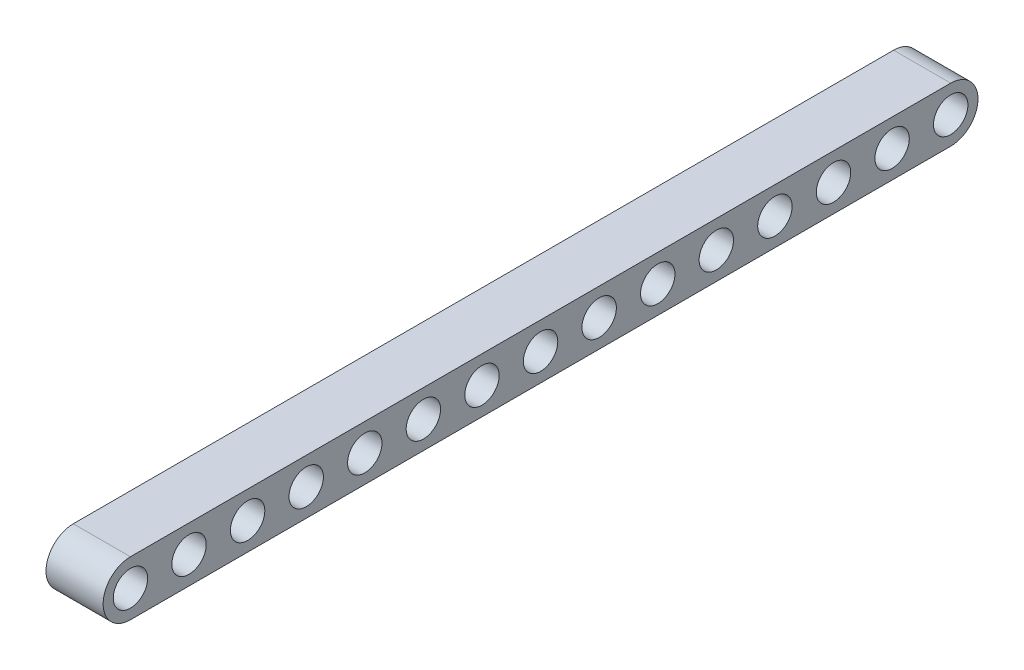
SolidWorks part; units mm, degrees
ref_plane "Front Plane" through (0, 0, 0) normal (0, 0, 1) x (1, 0, 0)
ref_plane "Top Plane" through (0, 0, 0) normal (0, 1, 0) x (1, 0, 0)
ref_plane "Right Plane" through (0, 0, 0) normal (1, 0, 0) x (0, 0, -1)
sketch "Sketch1" plane through (0, 0, 0) normal (1, 0, 0) x (0, 0, -1)
  line L0 (-56, 0) -> (56, 0) construction
  line L1 (-56, 3.73) -> (56, 3.73) construction
  line L2 (-56, 3.73) -> (-56, -3.73) construction
  line L3 (-56, -3.73) -> (56, -3.73) construction
  line L4 (56, 3.73) -> (56, -3.73) construction
  line L5 (-56, 3.73) -> (56, -3.73) construction
  line L6 (-56, -3.73) -> (56, 3.73) construction
  line L8 (-56, -3.73) -> (56, -3.73)
  line L10 (-56, 3.73) -> (56, 3.73)
  line L12 (-56, -3.73) -> (56, 3.73) construction
  line L13 (-56, 3.73) -> (56, -3.73) construction
  circle A0 centre (-56, 0) radius 2.35
  circle A1 centre (-48, 0) radius 2.35
  circle A2 centre (-40, 0) radius 2.35
  circle A3 centre (-32, 0) radius 2.35
  circle A4 centre (-24, 0) radius 2.35
  circle A5 centre (-16, 0) radius 2.35
  circle A6 centre (-8, 0) radius 2.35
  circle A7 centre (0, 0) radius 2.35
  circle A8 centre (8, 0) radius 2.35
  circle A9 centre (16, 0) radius 2.35
  circle A10 centre (24, 0) radius 2.35
  circle A11 centre (32, 0) radius 2.35
  arc A12 (-56, 3.73) -> (-56, -3.73) centre (-56, 0) ccw
  arc A13 (56, -3.73) -> (56, 3.73) centre (56, 0) ccw
  circle A14 centre (40, 0) radius 2.35
  circle A15 centre (48, 0) radius 2.35
  circle A16 centre (56, 0) radius 2.35
  point P0 (0, 0)
  point P9 (0, 0)
  dimension "D3" = 4.7
  dimension "D5" = 8
  dimension "D1" = 112
  dimension "D2" = 7.46
  dimension "D4" = 15
extrude "Boss-Extrude1" add sketch "Sketch1" along normal blind 7.8
